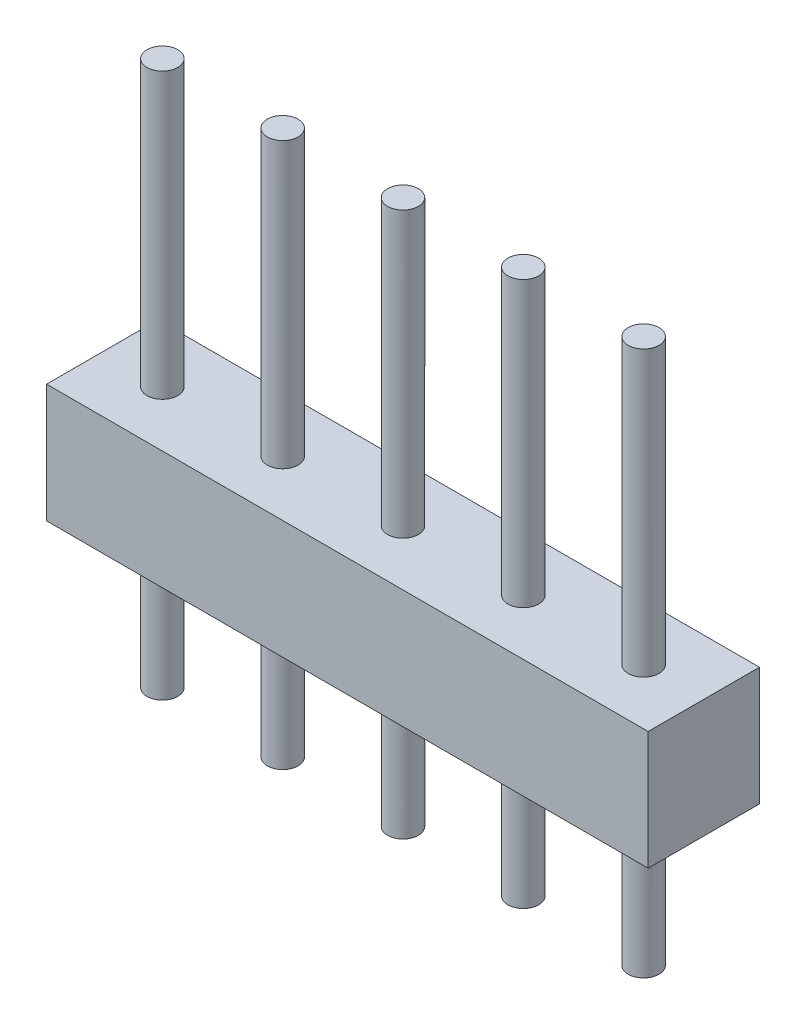
SolidWorks part; units mm, degrees
ref_plane "Plan de face" through (0, 0, 0) normal (0, 0, 1) x (1, 0, 0)
ref_plane "Plan de dessus" through (0, 0, 0) normal (0, 1, 0) x (1, 0, 0)
ref_plane "Plan de droite" through (0, 0, 0) normal (1, 0, 0) x (0, 0, -1)
sketch "Esquisse1" plane through (0, 0, 0) normal (0, 1, 0) x (1, 0, 0)
  line L1 (0, 0) -> (2.54, 0)
  line L2 (0, 0) -> (0, 2.35)
  line L3 (0, 2.35) -> (2.54, 2.35)
  line L4 (2.54, 0) -> (2.54, 2.35)
  dimension "D1" = 2.54
  dimension "D2" = 2.35
extrude "Boss.-Extru.1" add sketch "Esquisse1" along normal blind 2.5
sketch "Esquisse2" plane through (0, 0, 0) normal (0, 1, 0) x (1, 0, 0)
  line L0 (0, 1.175) -> (2.54, 1.175) construction
  line L1 (0, 2.35) -> (0, 0) construction
  line L2 (2.54, 0) -> (2.54, 2.35) construction
  circle A0 centre (1.27, 1.175) radius 0.325
  dimension "D1" = 0.65
extrude "Boss.-Extru.2" add sketch "Esquisse2" along normal blind 8.5 and the other way blind 3
chamfer "Chanfrein1" [suppressed] distance 0.3 angle 45
pattern_linear "Répétition linéaire1" count 5 spacing 2.54 along (1, 0, 0) of "Boss.-Extru.1", "Boss.-Extru.2"
